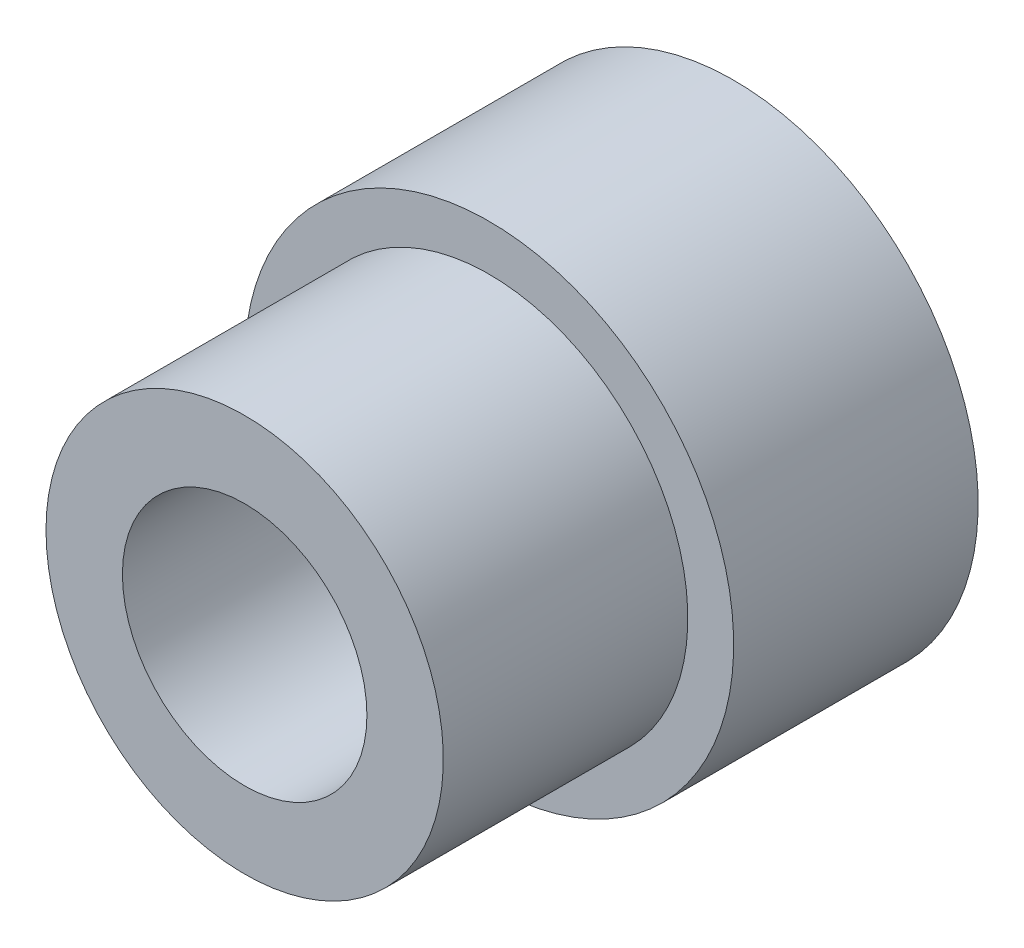
SolidWorks part; units mm, degrees
ref_plane "Front Plane" through (0, 0, 0) normal (0, 0, 1) x (1, 0, 0)
ref_plane "Top Plane" through (0, 0, 0) normal (0, 1, 0) x (1, 0, 0)
ref_plane "Right Plane" through (0, 0, 0) normal (1, 0, 0) x (0, 0, -1)
sketch "Sketch1" plane through (0, 0, 0) normal (0, 0, 1) x (1, 0, 0)
  circle A0 centre (0, 0) radius 9.525
  dimension "D1" = 19.05
extrude "Boss-Extrude1" add sketch "Sketch1" along normal blind 9.525
sketch "Sketch2" plane through (0, 0, 9.525) normal (0, 0, 1) x (1, 0, 0)
  circle A0 centre (0, 0) radius 7.7391
  dimension "D1" = 15.4781
extrude "Boss-Extrude2" add sketch "Sketch2" along normal blind 9.525
sketch "Sketch3" plane through (0, 0, 19.05) normal (0, 0, 1) x (1, 0, 0)
  circle A0 centre (0, 0) radius 4.7625
  dimension "D1" = 9.525
extrude "Cut-Extrude1" cut sketch "Sketch3" against normal through all
